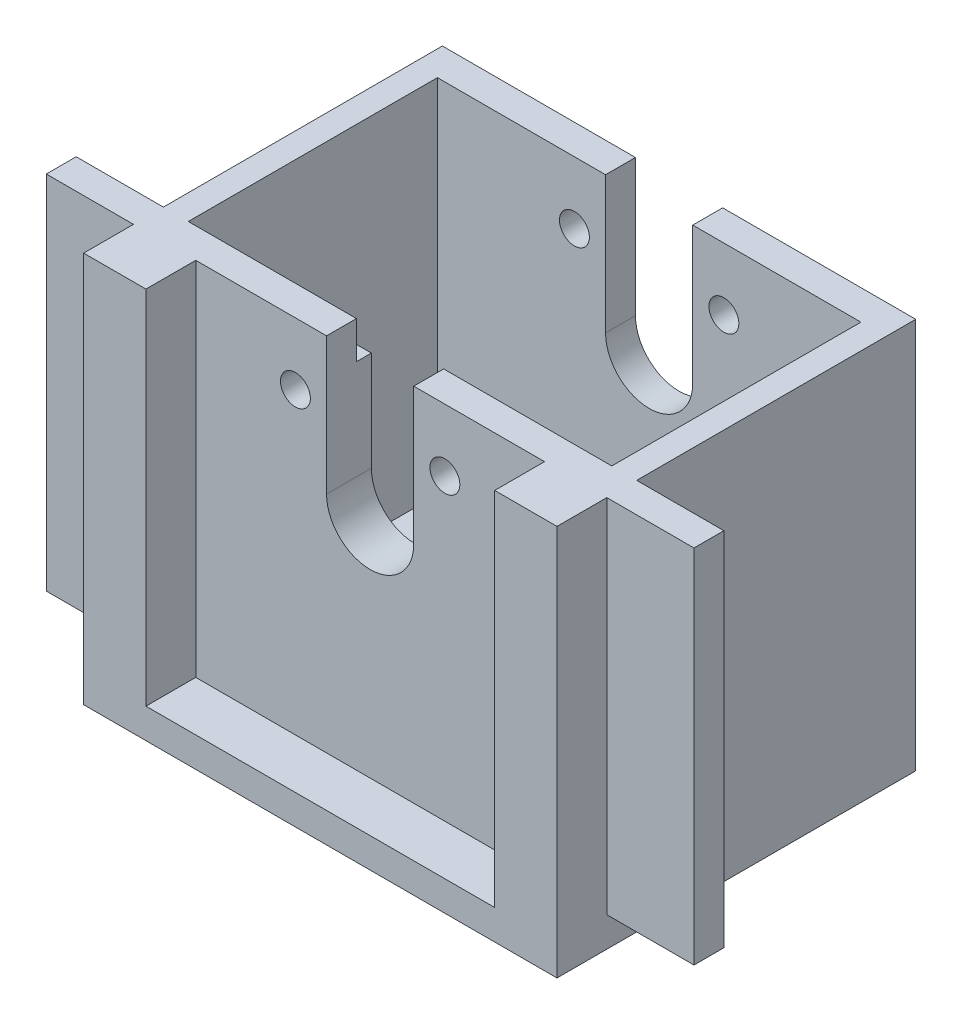
SolidWorks part; units mm, degrees
ref_plane "前视基准面" through (0, 0, 0) normal (0, 0, 1) x (1, 0, 0)
ref_plane "上视基准面" through (0, 0, 0) normal (0, 1, 0) x (1, 0, 0)
ref_plane "右视基准面" through (0, 0, 0) normal (1, 0, 0) x (0, 0, -1)
sketch "草图1" plane through (0, 0, 0) normal (0, 1, 0) x (1, 0, 0)
  line L1 (-95, 72) -> (95, 72)
  line L2 (-95, 72) -> (-95, -72)
  line L3 (-95, -72) -> (95, -72)
  line L4 (95, 72) -> (95, -72)
  circle A0 centre (-57, 41) radius 6
  circle A1 centre (57, 41) radius 6
  circle A2 centre (-57, -2) radius 6
  circle A3 centre (57, -2) radius 6
  dimension "D5" = 12
  dimension "D1" = 95
  dimension "D2" = 95
  dimension "D3" = 72
  dimension "D4" = 72
  dimension "D6" = 70
  dimension "D7" = 57
  dimension "D8" = 57
  dimension "D9" = 43
extrude "凸台-拉伸1" add sketch "草图1" along normal blind 12
sketch "草图2" plane through (0, 12, 0) normal (0, 1, 0) x (1, 0, 0)
  line L0 (0, -928) -> (0, 49072) construction
  line L1 (95, 72) -> (-95, 72) construction
  line L2 (95, -72) -> (95, 72) construction
  line L3 (-95, 72) -> (95, 72)
  line L4 (-95, 72) -> (-95, 60)
  line L5 (-95, 60) -> (95, 60)
  line L6 (95, 72) -> (95, 60)
  line L7 (-95, -72) -> (95, -72) construction
  line L8 (-130, -40) -> (130, -40)
  line L9 (-130, -40) -> (-130, -52)
  line L10 (-130, -52) -> (130, -52)
  line L11 (130, -40) -> (130, -52)
  point P5 (0, 72)
  dimension "D1" = 12
  dimension "D2" = 12
  dimension "D3" = 260
  dimension "D4" = 32
extrude "凸台-拉伸2" add sketch "草图2" along normal blind 145
sketch "草图3" plane through (0, 0, 52) normal (0, 0, 1) x (1, 0, 0)
  line L0 (0, -843) -> (0, 49157) construction
  line L1 (-130, 157) -> (130, 157) construction
  line L2 (-17.5, 157) -> (17.5, 157)
  line L3 (17.5, 157) -> (17.5, 102)
  line L4 (-17.5, 157) -> (-17.5, 102)
  arc A0 (17.5, 102) -> (-17.5, 102) centre (0, 102) cw
  circle A1 centre (-30, 132) radius 6
  circle A2 centre (30, 132) radius 6
  point P5 (0, 157)
  dimension "D3" = 12
  dimension "D4" = 12
  dimension "D1" = 55
  dimension "D2" = 35
  dimension "D5" = 30
  dimension "D6" = 60
extrude "切除-拉伸1" cut sketch "草图3" against normal through all
sketch "草图4" plane through (0, 0, 40) normal (0, 0, -1) x (-1, 0, 0)
  line L0 (-17.5, 142) -> (-39.5, 142)
  line L1 (-17.5, 102) -> (-17.5, 157) construction
  line L2 (-39.5, 142) -> (-39.5, 102)
  line L3 (-17.5, 142) -> (-17.5, 102)
  line L4 (17.5, 102) -> (17.5, 142)
  line L5 (17.5, 157) -> (17.5, 102) construction
  line L6 (17.5, 142) -> (39.5, 142)
  line L7 (39.5, 142) -> (39.5, 102)
  arc A0 (-39.5, 102) -> (39.5, 102) centre (0, 102) ccw
  arc A1 (17.5, 102) -> (-17.5, 102) centre (0, 102) cw
  circle A2 centre (-30, 132) radius 6
  circle A3 centre (30, 132) radius 6
  circle A4 centre (30, 132) radius 6 construction
  circle A5 centre (-30, 132) radius 6 construction
  dimension "D1" = 79
  dimension "D2" = 40
extrude "凸台-拉伸3" add sketch "草图4" along normal blind 6
sketch "草图5" plane through (0, 157, 0) normal (0, 1, 0) x (1, 0, 0)
  line L0 (-17.5, -40) -> (-130, -40) construction
  line L1 (-95, 60) -> (-85, 60)
  line L2 (-95, 60) -> (-95, -40)
  line L3 (-95, -40) -> (-85, -40)
  line L4 (-85, 60) -> (-85, -40)
  line L5 (95, -40) -> (-95, -40) construction
  line L6 (95, 60) -> (85, 60)
  line L7 (95, 60) -> (95, -40)
  line L8 (95, -40) -> (85, -40)
  line L9 (85, 60) -> (85, -40)
  dimension "D1" = 10
  dimension "D2" = 10
extrude "凸台-拉伸4" add sketch "草图5" against normal blind 145
sketch "草图6" plane through (0, 12, 0) normal (0, 1, 0) x (1, 0, 0)
  line L0 (-130, -52) -> (-17.5, -52) construction
  line L1 (-95, -72) -> (-70, -72)
  line L2 (-95, -72) -> (-95, -52)
  line L3 (-95, -52) -> (-70, -52)
  line L4 (-70, -72) -> (-70, -52)
  line L5 (-95, -52) -> (95, -52) construction
  line L6 (95, -72) -> (70, -72)
  line L7 (95, -72) -> (95, -52)
  line L8 (95, -52) -> (70, -52)
  line L9 (70, -72) -> (70, -52)
  dimension "D1" = 25
  dimension "D2" = 25
extrude "凸台-拉伸5" add sketch "草图6" along normal blind 145
